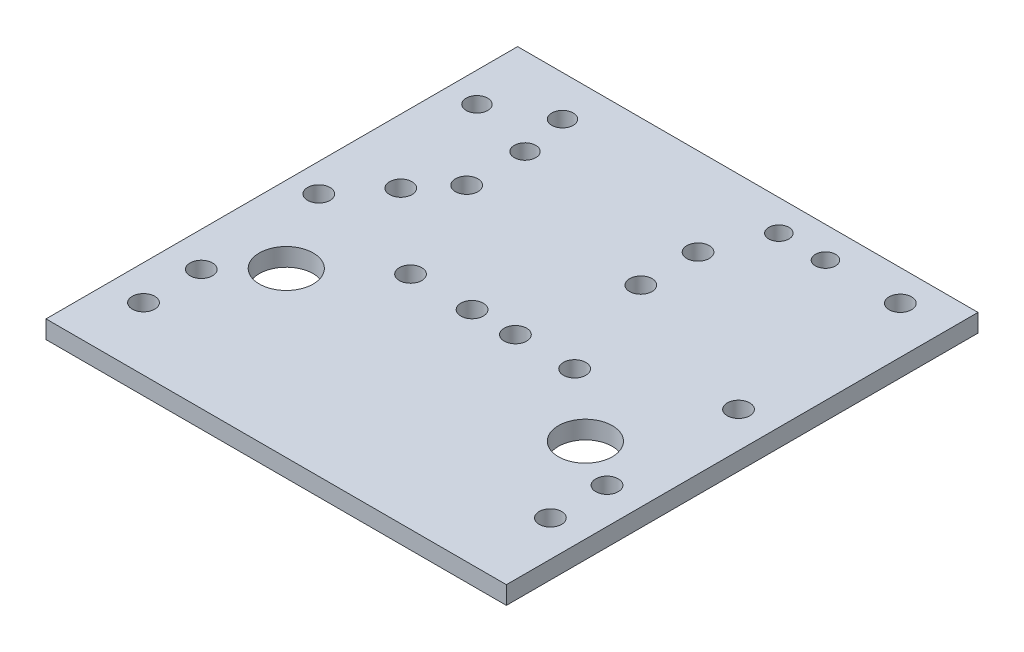
SolidWorks part; units mm, degrees
ref_plane "Plano frontal" through (0, 0, 0) normal (0, 0, 1) x (1, 0, 0)
ref_plane "Plano superior" through (0, 0, 0) normal (0, 1, 0) x (1, 0, 0)
ref_plane "Plano direito" through (0, 0, 0) normal (1, 0, 0) x (0, 0, -1)
sketch "Esboço1" plane through (0, 0, 0) normal (0, 1, 0) x (1, 0, 0)
  line L1 (-10.25, -10.5) -> (10.25, -10.5)
  line L2 (-10.25, -10.5) -> (-10.25, 10.5)
  line L3 (-10.25, 10.5) -> (10.25, 10.5)
  line L4 (10.25, -10.5) -> (10.25, 10.5)
  line L5 (-10.25, -10.5) -> (10.25, 10.5) construction
  line L6 (-10.25, 10.5) -> (10.25, -10.5) construction
  point P0 (0, 0)
  dimension "D1" = 20.5
  dimension "D2" = 21
extrude "Ressalto-extrusão1" add sketch "Esboço1" along normal blind 0.8
sketch "Esboço2" plane through (0, 0.8, 0) normal (0, 1, 0) x (1, 0, 0)
  circle A0 centre (8.1696, 9.1214) radius 0.5
  circle A1 centre (8.6563, 1.4303) radius 0.5
  circle A2 centre (8.6563, -4.4255) radius 0.5
  circle A3 centre (8.6563, -6.9466) radius 0.5
  circle A4 centre (6.4756, -3.2078) radius 1.2
  circle A5 centre (-6.8445, -3.2078) radius 1.2
  circle A6 centre (-8.7017, -5.134) radius 0.5
  circle A7 centre (-8.7017, -7.7063) radius 0.5
  circle A8 centre (4.8366, 9.1214) radius 0.45
  circle A9 centre (2.7617, 9.1214) radius 0.45
  circle A10 centre (1.6914, 6.5931) radius 0.5
  circle A11 centre (-8.9941, 0.3925) radius 0.5
  circle A12 centre (-3.8601, -0.6578) radius 0.5
  circle A13 centre (-1.1203, -0.6578) radius 0.5
  circle A14 centre (0.8097, -0.6578) radius 0.5
  circle A15 centre (3.4461, -0.6578) radius 0.5
  circle A16 centre (1.6914, 4.0453) radius 0.5
  circle A17 centre (-6.4519, 8.7006) radius 0.4788
  circle A18 centre (-6.0383, 6.619) radius 0.4788
  circle A19 centre (-8.9296, 7.3684) radius 0.4788
  circle A20 centre (-6.0383, 4.0177) radius 0.5
  circle A21 centre (-7.3921, 2.4398) radius 0.5
  dimension "D1" = 1
  dimension "D2" = 1
  dimension "D3" = 1
  dimension "D4" = 1
  dimension "D5" = 1
  dimension "D6" = 2.4
  dimension "D7" = 2.4
  dimension "D8" = 1
  dimension "D9" = 0.9
  dimension "D10" = 0.9
  dimension "D11" = 1
  dimension "D12" = 1
  dimension "D13" = 1
  dimension "D14" = 1
extrude "Corte-extrusão1" cut sketch "Esboço2" against normal mid plane 10
